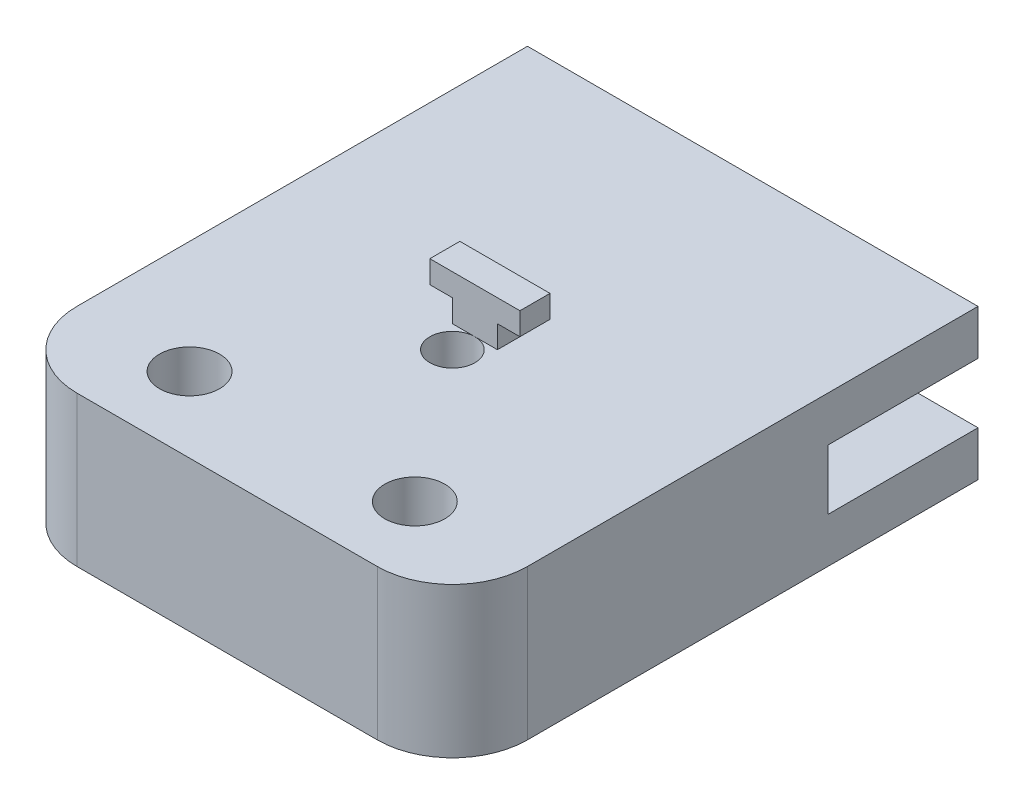
SolidWorks part; units mm, degrees
ref_plane "Alzado" through (0, 0, 0) normal (0, 0, 1) x (1, 0, 0)
ref_plane "Planta" through (0, 0, 0) normal (0, 1, 0) x (1, 0, 0)
ref_plane "Vista lateral" through (0, 0, 0) normal (1, 0, 0) x (0, 0, -1)
sketch "Croquis1" plane through (0, 0, 0) normal (0, 1, 0) x (1, 0, 0)
  line L0 (0, 30) -> (5, 30) construction
  line L1 (0, 0) -> (30, 0)
  line L2 (0, 0) -> (0, 35)
  line L3 (0, 35) -> (30, 35)
  line L4 (30, 0) -> (30, 35)
  line L5 (5, 30) -> (25, 30) construction
  line L6 (25, 30) -> (30, 30) construction
  line L7 (15, 30) -> (15, 35) construction
  line L8 (0, 5) -> (7.5, 5) construction
  line L9 (7.5, 5) -> (22.5, 5) construction
  line L10 (22.5, 5) -> (30, 5) construction
  line L11 (15, 30) -> (15, 5) construction
  circle A2 centre (7.5, 5) radius 2
  circle A3 centre (22.5, 5) radius 2
  dimension "D6" = 4
  dimension "D1" = 30
  dimension "D2" = 35
  dimension "D4" = 20
  dimension "D5" = 5
  dimension "D7" = 15
  dimension "D8" = 5
extrude "Saliente-Extruir1" add sketch "Croquis1" along normal blind 10
sketch "Croquis2" plane through (30, 0, 0) normal (1, 0, 0) x (0, 0, -1)
  line L0 (35, 10) -> (35, 0) construction
  line L1 (35, 3) -> (25, 3)
  line L2 (35, 3) -> (35, 7)
  line L3 (35, 7) -> (25, 7)
  line L4 (25, 3) -> (25, 7)
  line L5 (0, 10) -> (35, 10) construction
  dimension "D1" = 10
  dimension "D2" = 4
  dimension "D3" = 3
extrude "Cortar-Extruir1" cut sketch "Croquis2" against normal blind 41
fillet "Redondeo1" radius 5 2 edges at (30, 5, 0) (0, 5, 0)
sketch "Croquis3" plane through (0, 10, 0) normal (0, 1, 0) x (1, 0, 0)
  line L0 (7.5, 5) -> (22.5, 5) construction
  line L1 (15, 5) -> (15, 25) construction
  line L2 (0, 25) -> (30, 25) construction
  circle A0 centre (15, 15) radius 1.5
  dimension "D1" = 3
extrude "Cortar-Extruir2" cut sketch "Croquis3" against normal blind 10
sketch "Croquis4" plane through (0, 10, 0) normal (0, 1, 0) x (1, 0, 0)
  line L0 (15, 15) -> (15, 18.5) construction
  line L1 (12, 16.5) -> (18, 16.5)
  line L2 (12, 16.5) -> (12, 18.5)
  line L3 (12, 18.5) -> (18, 18.5)
  line L4 (18, 16.5) -> (18, 18.5)
  circle A0 centre (15, 15) radius 1.5 construction
  point P4 (15, 16.5)
  dimension "D1" = 2
  dimension "D2" = 6
extrude "Saliente-Extruir2" add sketch "Croquis4" along normal blind 3
sketch "Croquis5" plane through (0, 0, -16.5) normal (0, 0, 1) x (1, 0, 0)
  line L1 (18, 10) -> (16.5, 10)
  line L2 (18, 10) -> (18, 11.5)
  line L3 (18, 11.5) -> (16.5, 11.5)
  line L4 (16.5, 10) -> (16.5, 11.5)
  line L5 (12, 10) -> (13.5, 10)
  line L6 (12, 10) -> (12, 11.5)
  line L7 (12, 11.5) -> (13.5, 11.5)
  line L8 (13.5, 10) -> (13.5, 11.5)
  line L9 (16.5, 0) -> (16.5, 10) construction
  dimension "D1" = 1.5
extrude "Cortar-Extruir3" cut sketch "Croquis5" against normal blind 3
